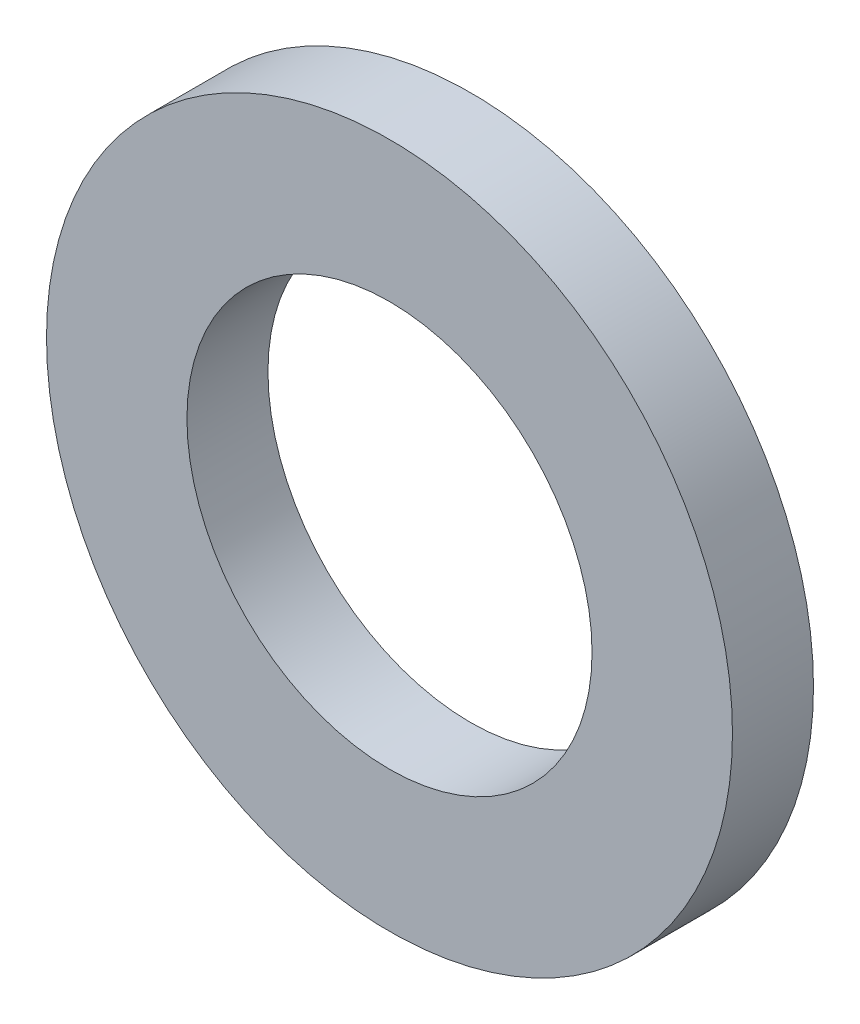
SolidWorks part; units mm, degrees
material "VITON"
ref_plane "前视基准面" through (0, 0, 0) normal (0, 0, 1) x (1, 0, 0)
ref_plane "上视基准面" through (0, 0, 0) normal (0, 1, 0) x (1, 0, 0)
ref_plane "右视基准面" through (0, 0, 0) normal (1, 0, 0) x (0, 0, -1)
other "Configuration Table"
sketch "草图1" plane through (0, 0, 0) normal (0, 0, 1) x (1, 0, 0)
  circle A0 centre (0, 0) radius 60
  circle A1 centre (0, 0) radius 101.6
  dimension "D1" = 120
  dimension "D2" = 203.2
extrude "凸台-拉伸1" add sketch "草图1" along normal blind 24
